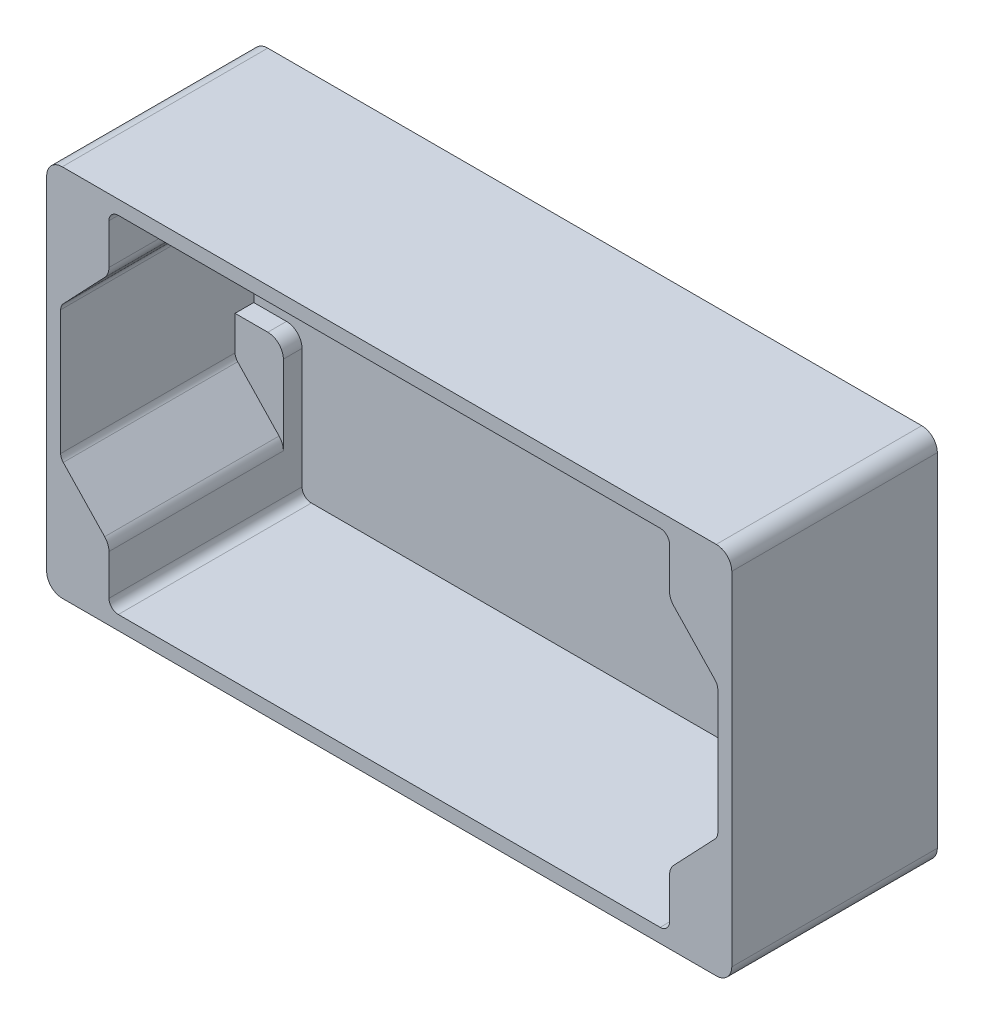
SolidWorks part; units mm, degrees
material "ألمنيوم خلائطي"
ref_plane "Front" through (0, 0, 0) normal (0, 0, 1) x (1, 0, 0)
ref_plane "Top" through (0, 0, 0) normal (0, 1, 0) x (1, 0, 0)
ref_plane "Right" through (0, 0, 0) normal (1, 0, 0) x (0, 0, -1)
sketch "Sketch1" plane through (0, 0, 0) normal (0, 0, 1) x (1, 0, 0)
  line L1 (110, 60) -> (-110, 60)
  line L2 (110, 60) -> (110, -60)
  line L3 (110, -60) -> (-110, -60)
  line L4 (-110, 60) -> (-110, -60)
  line L5 (110, 60) -> (-110, -60) construction
  line L6 (110, -60) -> (-110, 60) construction
  point P0 (0, 0)
  dimension "D1" = 220
  dimension "D2" = 120
extrude "Boss-Extrude1" add sketch "Sketch1" along normal mid plane 66
sketch "Sketch2" plane through (0, 0, 33) normal (0, 0, 1) x (1, 0, 0)
  line L0 (0, 60) -> (0, 0) construction
  line L1 (110, 60) -> (-110, 60) construction
  line L2 (0, 0) -> (110, 0) construction
  line L3 (110, -60) -> (110, 60) construction
  line L4 (-87, 55.5) -> (87, 55.5)
  line L5 (90, 52.5) -> (90, 39.4969)
  line L6 (91.3757, 36.0525) -> (104.6746, 22.059)
  line L7 (105.5, 19.9923) -> (105.5, -19.9923)
  line L8 (-90, 52.5) -> (-90, 39.4969)
  line L9 (-91.3757, 36.0525) -> (-104.6746, 22.059)
  line L10 (-105.5, 19.9923) -> (-105.5, -19.9923)
  line L11 (-90, -52.5) -> (-90, -39.4969)
  line L12 (91.3757, -36.0525) -> (104.6746, -22.059)
  line L13 (90, -52.5) -> (90, -39.4969)
  line L14 (-87, -55.5) -> (87, -55.5)
  line L15 (-91.3757, -36.0525) -> (-104.6746, -22.059)
  arc A0 (104.6746, 22.059) -> (105.5, 19.9923) centre (102.5, 19.9923) cw
  arc A1 (90, 52.5) -> (87, 55.5) centre (87, 52.5) ccw
  arc A2 (90, 39.4969) -> (91.3757, 36.0525) centre (95, 39.4969) ccw
  arc A3 (-90, 52.5) -> (-87, 55.5) centre (-87, 52.5) cw
  arc A4 (-90, 39.4969) -> (-91.3757, 36.0525) centre (-95, 39.4969) cw
  arc A5 (-104.6746, 22.059) -> (-105.5, 19.9923) centre (-102.5, 19.9923) ccw
  arc A6 (-90, -39.4969) -> (-91.3757, -36.0525) centre (-95, -39.4969) ccw
  arc A7 (-90, -52.5) -> (-87, -55.5) centre (-87, -52.5) ccw
  arc A8 (90, -39.4969) -> (91.3757, -36.0525) centre (95, -39.4969) cw
  arc A9 (90, -52.5) -> (87, -55.5) centre (87, -52.5) cw
  arc A10 (104.6746, -22.059) -> (105.5, -19.9923) centre (102.5, -19.9923) ccw
  arc A11 (-104.6746, -22.059) -> (-105.5, -19.9923) centre (-102.5, -19.9923) cw
  point P13 (0, -55.5)
  point P15 (105.5, 21.1905)
  point P18 (90, 55.5)
  point P21 (90, 37.5)
  point P32 (0, 55.5)
  point P47 (105.5, 0)
  point P48 (90, -37.5)
  point P49 (90, -55.5)
  point P50 (105.5, -21.1905)
  point P54 (-105.5, 0)
  dimension "D6" = 3
  dimension "D7" = 5
  dimension "D1" = 4.5
  dimension "D2" = 4.5
  dimension "D3" = 18
  dimension "D4" = 22.5
  dimension "D5" = 90
extrude "Cut-Extrude1" cut sketch "Sketch2" against normal blind 56
sketch "Sketch3" plane through (0, 0, -23) normal (0, 0, 1) x (1, 0, 0)
  line L0 (-90, 39.4969) -> (-90, 14)
  line L1 (-95, 9) -> (-105.5, 9)
  line L2 (0, 0) -> (-105.5, 0) construction
  line L3 (0, 0) -> (0, 55.5) construction
  line L4 (-90, -39.4969) -> (-90, -14)
  line L5 (-95, -9) -> (-105.5, -9)
  line L6 (90, -39.4969) -> (90, -14)
  line L7 (95, -9) -> (105.5, -9)
  line L8 (95, 9) -> (105.5, 9)
  line L9 (90, 39.4969) -> (90, 14)
  line L12 (104.6746, 22.059) -> (91.3757, 36.0525)
  line L13 (90, 39.4969) -> (90, 52.5)
  line L14 (87, 55.5) -> (-87, 55.5)
  line L15 (-90, 52.5) -> (-90, 39.4969)
  line L16 (-91.3757, 36.0525) -> (-104.6746, 22.059)
  line L17 (-105.5, 19.9923) -> (-105.5, -19.9923)
  line L18 (-104.6746, -22.059) -> (-91.3757, -36.0525)
  line L19 (-90, -39.4969) -> (-90, -52.5)
  line L20 (-87, -55.5) -> (87, -55.5)
  line L21 (90, -52.5) -> (90, -39.4969)
  line L22 (91.3757, -36.0525) -> (104.6746, -22.059)
  line L23 (105.5, -19.9923) -> (105.5, 19.9923)
  line L24 (104.6746, 22.059) -> (91.3757, 36.0525)
  line L25 (90, 39.4969) -> (90, 52.5)
  line L26 (87, 55.5) -> (-87, 55.5)
  line L27 (-90, 52.5) -> (-90, 39.4969)
  line L28 (-91.3757, 36.0525) -> (-104.6746, 22.059)
  line L29 (-105.5, 19.9923) -> (-105.5, -19.9923)
  line L30 (-104.6746, -22.059) -> (-91.3757, -36.0525)
  line L31 (-90, -39.4969) -> (-90, -52.5)
  line L32 (-87, -55.5) -> (87, -55.5)
  line L33 (90, -52.5) -> (90, -39.4969)
  line L34 (91.3757, -36.0525) -> (104.6746, -22.059)
  line L35 (105.5, -19.9923) -> (105.5, 19.9923)
  arc A0 (-90, 14) -> (-95, 9) centre (-95, 14) cw
  arc A1 (-90, -14) -> (-95, -9) centre (-95, -14) ccw
  arc A2 (90, -14) -> (95, -9) centre (95, -14) cw
  arc A3 (90, 14) -> (95, 9) centre (95, 14) ccw
  arc A12 (105.5, 19.9923) -> (104.6746, 22.059) centre (102.5, 19.9923) ccw
  arc A13 (90, 39.4969) -> (91.3757, 36.0525) centre (95, 39.4969) ccw
  arc A14 (90, 52.5) -> (87, 55.5) centre (87, 52.5) ccw
  arc A15 (-87, 55.5) -> (-90, 52.5) centre (-87, 52.5) ccw
  arc A16 (-91.3757, 36.0525) -> (-90, 39.4969) centre (-95, 39.4969) ccw
  arc A17 (-104.6746, 22.059) -> (-105.5, 19.9923) centre (-102.5, 19.9923) ccw
  arc A18 (-105.5, -19.9923) -> (-104.6746, -22.059) centre (-102.5, -19.9923) ccw
  arc A19 (-90, -39.4969) -> (-91.3757, -36.0525) centre (-95, -39.4969) ccw
  arc A20 (-90, -52.5) -> (-87, -55.5) centre (-87, -52.5) ccw
  arc A21 (87, -55.5) -> (90, -52.5) centre (87, -52.5) ccw
  arc A22 (91.3757, -36.0525) -> (90, -39.4969) centre (95, -39.4969) ccw
  arc A23 (104.6746, -22.059) -> (105.5, -19.9923) centre (102.5, -19.9923) ccw
  arc A24 (105.5, 19.9923) -> (104.6746, 22.059) centre (102.5, 19.9923) ccw
  arc A25 (90, 39.4969) -> (91.3757, 36.0525) centre (95, 39.4969) ccw
  arc A26 (90, 52.5) -> (87, 55.5) centre (87, 52.5) ccw
  arc A27 (-87, 55.5) -> (-90, 52.5) centre (-87, 52.5) ccw
  arc A28 (-91.3757, 36.0525) -> (-90, 39.4969) centre (-95, 39.4969) ccw
  arc A29 (-104.6746, 22.059) -> (-105.5, 19.9923) centre (-102.5, 19.9923) ccw
  arc A30 (-105.5, -19.9923) -> (-104.6746, -22.059) centre (-102.5, -19.9923) ccw
  arc A31 (-90, -39.4969) -> (-91.3757, -36.0525) centre (-95, -39.4969) ccw
  arc A32 (-90, -52.5) -> (-87, -55.5) centre (-87, -52.5) ccw
  arc A33 (87, -55.5) -> (90, -52.5) centre (87, -52.5) ccw
  arc A34 (91.3757, -36.0525) -> (90, -39.4969) centre (95, -39.4969) ccw
  arc A35 (104.6746, -22.059) -> (105.5, -19.9923) centre (102.5, -19.9923) ccw
  point P26 (-90, 9)
  point P49 (-90, -9)
  point P54 (90, -9)
  line M34 (90, 39.4969) -> (90, 52.5)
  arc M35 (90, 52.5) -> (87, 55.5) centre (87, 52.5) ccw
  line M36 (87, 55.5) -> (-87, 55.5)
  arc M37 (-87, 55.5) -> (-90, 52.5) centre (-87, 52.5) ccw
  line M38 (-90, 52.5) -> (-90, 39.4969)
  line M42 (-105.5, 19.9923) -> (-105.5, -19.9923)
  line M46 (-90, -39.4969) -> (-90, -52.5)
  arc M47 (-90, -52.5) -> (-87, -55.5) centre (-87, -52.5) ccw
  line M48 (-87, -55.5) -> (87, -55.5)
  arc M49 (87, -55.5) -> (90, -52.5) centre (87, -52.5) ccw
  line M50 (90, -52.5) -> (90, -39.4969)
  line M54 (105.5, -19.9923) -> (105.5, 19.9923)
  dimension "D3" = 5
  dimension "D4" = 5
  dimension "D2" = 9
  dimension "D1" = 0
extrude "Cut-Extrude2" cut sketch "Sketch3" against normal blind 6 contours A3 L9 L0 A0 L1 L5 A1 L4 L6 A2 L7 L8 M34 M35 M36 M37 M38 M42 M46 M47 M48 M49 M50 M54
fillet "Fillet1" radius 5 4 edges at (110, -60, 0) (-110, -60, 0) (-110, 60, 0) (110, 60, 0)
sketch "Sketch4" [suppressed] plane through (0, 0, 33) normal (0, 0, 1) x (1, 0, 0)
  line L4 (-105, -60) -> (105, -60)
  line L5 (110, -55) -> (110, 55)
  line L6 (105, 60) -> (-105, 60)
  line L7 (-110, 55) -> (-110, -55)
  line L8 (-105, -60) -> (105, -60)
  line L9 (110, -55) -> (110, 55)
  line L10 (105, 60) -> (-105, 60)
  line L11 (-110, 55) -> (-110, -55)
  arc A4 (105, -60) -> (110, -55) centre (105, -55) ccw
  arc A5 (110, 55) -> (105, 60) centre (105, 55) ccw
  arc A6 (-105, 60) -> (-110, 55) centre (-105, 55) ccw
  arc A7 (-110, -55) -> (-105, -60) centre (-105, -55) ccw
  arc A8 (105, -60) -> (110, -55) centre (105, -55) ccw
  arc A9 (110, 55) -> (105, 60) centre (105, 55) ccw
  arc A10 (-105, 60) -> (-110, 55) centre (-105, 55) ccw
  arc A11 (-110, -55) -> (-105, -60) centre (-105, -55) ccw
  dimension "D1" = 0
extrude "Boss-Extrude2" [suppressed] add sketch "Sketch4" along normal blind 29
